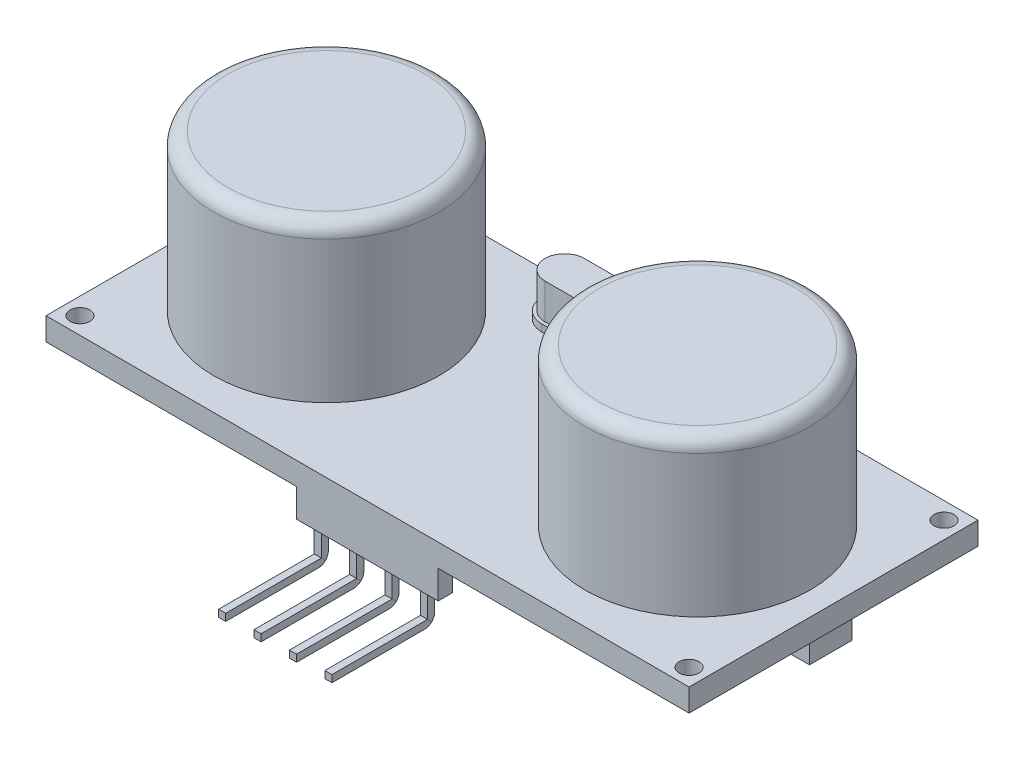
SolidWorks part; units mm, degrees
ref_plane "Alzado" through (0, 0, 0) normal (0, 0, 1) x (1, 0, 0)
ref_plane "Planta" through (0, 0, 0) normal (0, 1, 0) x (1, 0, 0)
ref_plane "Vista lateral" through (0, 0, 0) normal (1, 0, 0) x (0, 0, -1)
sketch "Croquis1" plane through (0, 0, 0) normal (0, 1, 0) x (1, 0, 0)
  line L1 (-22.7, 10.2) -> (22.7, 10.2)
  line L2 (-22.7, 10.2) -> (-22.7, -10.2)
  line L3 (-22.7, -10.2) -> (22.7, -10.2)
  line L4 (22.7, 10.2) -> (22.7, -10.2)
  line L5 (-22.7, 10.2) -> (22.7, -10.2) construction
  line L6 (-22.7, -10.2) -> (22.7, 10.2) construction
  point P0 (0, 0)
  dimension "D1" = 45.4
  dimension "D2" = 20.4
extrude "Saliente-Extruir1" add sketch "Croquis1" along normal blind 1.6
sketch "Croquis2" plane through (0, 1.6, 0) normal (0, 1, 0) x (1, 0, 0)
  line L5 (-21.5, 9) -> (21.5, -9) construction
  line L6 (-21.5, -9) -> (21.5, 9) construction
  circle A0 centre (-21.5, 9) radius 0.7
  circle A1 centre (21.5, 9) radius 0.7
  circle A2 centre (21.5, -9) radius 0.7
  circle A3 centre (-21.5, -9) radius 0.7
  point P0 (0, 0)
  dimension "D3" = 1.4
  dimension "D1" = 43
  dimension "D2" = 18
extrude "Cortar-Extruir1" cut sketch "Croquis2" against normal blind 1
sketch "Croquis3" plane through (0, 1.6, 0) normal (0, 1, 0) x (1, 0, 0)
  line L0 (0, 10.2) -> (0, -10.2) construction
  line L1 (22.7, 10.2) -> (-22.7, 10.2) construction
  line L2 (-22.7, -10.2) -> (22.7, -10.2) construction
  line L3 (-4.2022, 7.9196) -> (4.2022, 7.9196) construction
  line L4 (-4.2022, 9.5358) -> (4.2022, 9.5358)
  line L5 (-4.2022, 6.3033) -> (4.2022, 6.3033)
  line L6 (-4.2022, 7.9196) -> (4.2022, 7.9196) construction
  line L7 (-4.2022, 9.3049) -> (4.2022, 9.3049)
  line L8 (-4.2022, 6.5342) -> (4.2022, 6.5342)
  arc A0 (-4.2022, 9.5358) -> (-4.2022, 6.3033) centre (-4.2022, 7.9196) ccw
  arc A1 (4.2022, 6.3033) -> (4.2022, 9.5358) centre (4.2022, 7.9196) ccw
  arc A2 (-4.2022, 9.3049) -> (-4.2022, 6.5342) centre (-4.2022, 7.9196) ccw
  arc A3 (4.2022, 6.5342) -> (4.2022, 9.3049) centre (4.2022, 7.9196) ccw
  point P8 (0, 7.9196)
  point P15 (0, 7.9196)
extrude "Saliente-Extruir2" add sketch "Croquis3" along normal blind 0.5 contours L8 A3 L7 A2 | L5 A1 L4 A0
sketch "Croquis8" plane through (0, 1.6, 0) normal (0, 1, 0) x (1, 0, 0)
  line L0 (-4.2022, 9.3049) -> (4.2022, 9.3049) construction
  line L1 (-4.2022, 6.5342) -> (4.2022, 6.5342) construction
  line L2 (-4.2022, 9.3049) -> (4.2022, 9.3049)
  line L3 (-4.2022, 6.5342) -> (4.2022, 6.5342)
  arc A0 (4.2022, 6.5342) -> (4.2022, 9.3049) centre (4.2022, 7.9196) ccw construction
  arc A1 (-4.2022, 9.3049) -> (-4.2022, 6.5342) centre (-4.2022, 7.9196) ccw construction
  arc A2 (4.2022, 6.5342) -> (4.2022, 9.3049) centre (4.2022, 7.9196) ccw
  arc A3 (-4.2022, 9.3049) -> (-4.2022, 6.5342) centre (-4.2022, 7.9196) ccw
extrude "Saliente-Extruir3" add sketch "Croquis8" along normal blind 3
sketch "Croquis9" plane through (0, 1.6, 0) normal (0, 1, 0) x (1, 0, 0)
  line L0 (-21.05, 0) -> (21.05, 0) construction
  line L3 (-22.7, 10.2) -> (0, -10.2) construction
  line L4 (-22.7, -10.2) -> (22.7, -10.2) construction
  line L5 (0, -10.2) -> (22.7, 10.2) construction
  line L6 (-22.7, -10.2) -> (0, 10.2) construction
  line L7 (22.7, 10.2) -> (-22.7, 10.2) construction
  line L8 (0, 10.2) -> (22.7, -10.2) construction
  circle A0 centre (-13.1, 0) radius 7.95
  circle A1 centre (13.1, 0) radius 7.95
  point P2 (0, 0)
  dimension "D1" = 15.9
  dimension "D2" = 15.9
  dimension "D3" = 42.1
extrude "Saliente-Extruir4" add sketch "Croquis9" along normal blind 11
sketch "Croquis10" plane through (0, 0, 0) normal (0, -1, 0) x (1, 0, 0)
  line L0 (0, 10.2) -> (0, -10.2) construction
  line L1 (-22.7, 10.2) -> (22.7, 10.2) construction
  line L2 (22.7, -10.2) -> (-22.7, -10.2) construction
  line L3 (22.7, 0) -> (-22.7, 0) construction
  line L4 (22.7, 10.2) -> (22.7, -10.2) construction
  line L5 (-22.7, -10.2) -> (-22.7, 10.2) construction
  line L6 (-5.0127, 10.2) -> (4.9873, 10.2)
  line L7 (-5.0127, 10.2) -> (-5.0127, 9.2)
  line L8 (-5.0127, 9.2) -> (4.9873, 9.2)
  line L9 (4.9873, 9.2) -> (4.9873, 10.2)
  point P15 (-0.0127, 10.2)
  dimension "D1" = 10
  dimension "D2" = 1
extrude "Saliente-Extruir5" add sketch "Croquis10" along normal blind 2
sketch "Croquis11" plane through (0, -2, 0) normal (0, -1, 0) x (1, 0, 0)
  line L0 (-5.0127, 10.2) -> (-0.0127, 10.2) construction
  line L1 (4.9873, 10.2) -> (-5.0127, 10.2) construction
  line L2 (-2.5127, 10.2) -> (-2.5127, 9.2) construction
  line L3 (-5.0127, 9.2) -> (4.9873, 9.2) construction
  line L4 (-5.0127, 10.2) -> (-2.5127, 9.2) construction
  line L5 (-2.5127, 10.2) -> (-5.0127, 9.2) construction
sketch3d "Croquis3D1"
  line L0 (-3.7627, -2, 9.7) -> (-3.7627, -4, 9.7)
  line L1 (-5.0127, -2, 10.2) -> (-2.5127, -2, 9.2) construction
  line L2 (-3.7627, -4, 9.7) -> (-3.7627, -4, 16.7)
  dimension "D1" = 7
  dimension "D2" = 2
sketch "Croquis12" plane through (0, -2, 0) normal (0, -1, 0) x (1, 0, 0)
  line L1 (-4.0127, 9.95) -> (-3.5127, 9.95)
  line L2 (-4.0127, 9.95) -> (-4.0127, 9.45)
  line L3 (-4.0127, 9.45) -> (-3.5127, 9.45)
  line L4 (-3.5127, 9.95) -> (-3.5127, 9.45)
  line L5 (-4.0127, 9.95) -> (-3.5127, 9.45) construction
  line L6 (-4.0127, 9.45) -> (-3.5127, 9.95) construction
  point P0 (-3.7627, 9.7)
  dimension "D1" = 0.5
sweep "Barrer1" add profiles "Croquis12" path "Croquis3D1"
fillet "Redondeo4" radius 0.7 1 edges at (-3.7627, -4.25, 9.45)
pattern_linear "MatrizL1" count 4 spacing 2.5 along (1, 0, 0) of "Barrer1"
fillet "Redondeo5" radius 1 2 edges at (13.1, 12.6, 7.95) (-13.1, 12.6, 7.95)
sketch "Croquis13" plane through (0, 0, 0) normal (0, -1, 0) x (1, 0, 0)
  line L1 (-4.5, 1.5) -> (4.5, 1.5)
  line L2 (-4.5, 1.5) -> (-4.5, -1.5)
  line L3 (-4.5, -1.5) -> (4.5, -1.5)
  line L4 (4.5, 1.5) -> (4.5, -1.5)
  line L5 (-4.5, 1.5) -> (4.5, -1.5) construction
  line L6 (-4.5, -1.5) -> (4.5, 1.5) construction
  point P0 (0, 0)
  dimension "D1" = 9
  dimension "D2" = 3
extrude "Saliente-Extruir6" add sketch "Croquis13" along normal blind 1.5
pattern_linear "MatrizL2" count 2 spacing 18 along (1, 0, 0) of "Saliente-Extruir6"
sketch "Croquis14" plane through (0, 0, 0) normal (0, -1, 0) x (1, 0, 0)
  line L0 (-22.7, -10.2) -> (-22.7, 10.2) construction
  line L1 (-20.7, 4.2078) -> (-17.7, 4.2078)
  line L2 (-20.7, 4.2078) -> (-20.7, -4.7922)
  line L3 (-20.7, -4.7922) -> (-17.7, -4.7922)
  line L4 (-17.7, 4.2078) -> (-17.7, -4.7922)
  line L5 (-20.7, 4.2078) -> (-17.7, -4.7922) construction
  line L6 (-20.7, -4.7922) -> (-17.7, 4.2078) construction
  point P0 (-19.2, -0.2922)
  dimension "D1" = 3
  dimension "D2" = 2
  dimension "D3" = 9
extrude "Saliente-Extruir7" add sketch "Croquis14" along normal blind 1.5
fillet "Redondeo6" radius 0.7 3 edges at (3.7373, -4.25, 9.45) (1.2373, -4.25, 9.45) (-1.2627, -4.25, 9.45)
sketch "Sketch1" plane through (0, 1.6, 0) normal (0, 1, 0) x (1, 0, 0)
  point P5 (13.1, 7.95)
